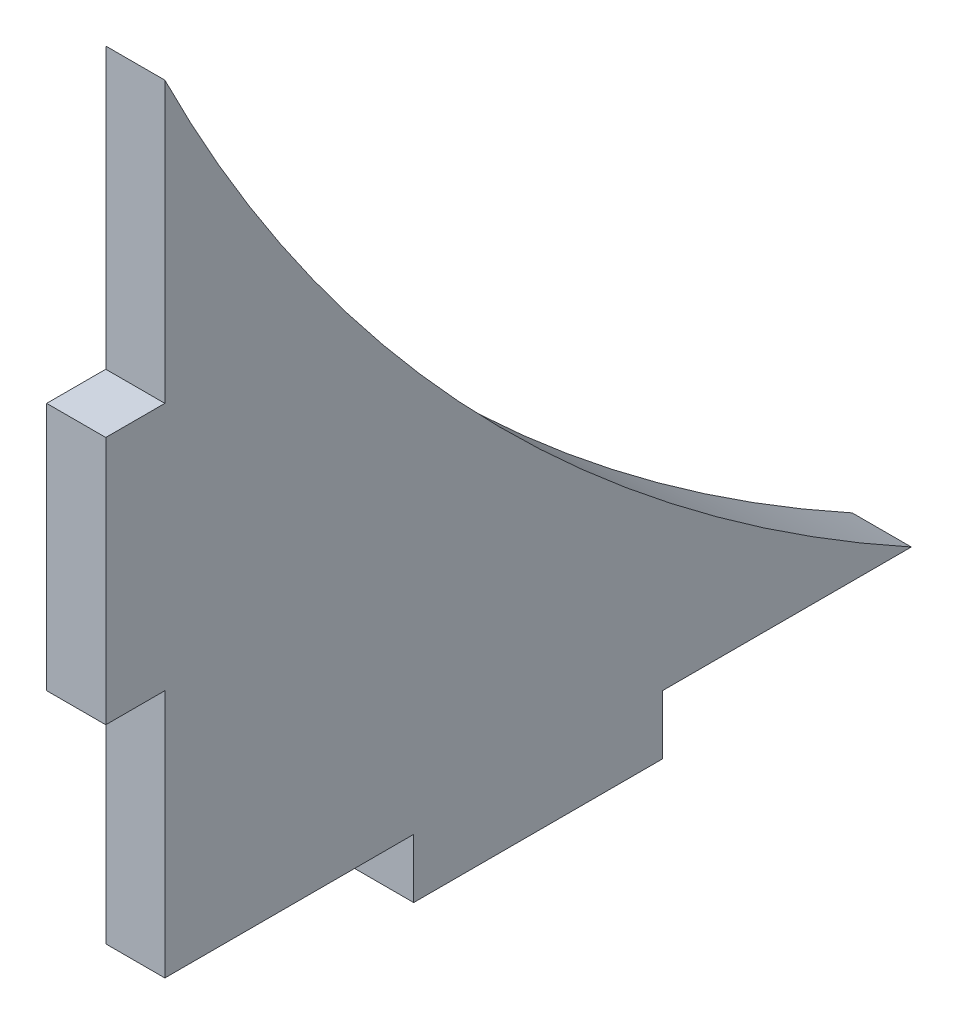
SolidWorks part; units mm, degrees
ref_plane "Front Plane" through (0, 0, 0) normal (0, 0, 1) x (1, 0, 0)
ref_plane "Top Plane" through (0, 0, 0) normal (0, 1, 0) x (1, 0, 0)
ref_plane "Right Plane" through (0, 0, 0) normal (1, 0, 0) x (0, 0, -1)
sketch "Sketch1" plane through (0, 0, 0) normal (1, 0, 0) x (0, 0, -1)
  line L0 (-143.7729, 109.4322) -> (-143.7729, -140.5678)
  line L1 (-143.7729, -140.5678) -> (96.2271, -140.5678)
  arc A0 (-143.7729, 109.4322) -> (96.2271, -140.5678) centre (373.8498, 366.15) ccw
  dimension "D1" = 250
  dimension "D2" = 240
extrude "Boss-Extrude1" add sketch "Sketch1" along normal blind 19
sketch "Sketch2" plane through (0, -140.5678, 0) normal (0, -1, 0) x (1, 0, 0)
  line L0 (0, 143.7729) -> (0, -96.2271) construction
  line L1 (0, 63.7729) -> (19, 63.7729)
  line L2 (0, 63.7729) -> (0, -16.2271)
  line L3 (0, -16.2271) -> (19, -16.2271)
  line L4 (19, 63.7729) -> (19, -16.2271)
  line L5 (19, 143.7729) -> (19, -96.2271) construction
  line L7 (19, 143.7729) -> (0, 143.7729) construction
  dimension "D2" = 80
extrude "Boss-Extrude2" add sketch "Sketch2" along normal blind 19
sketch "Sketch3" plane through (0, 0, 143.7729) normal (0, 0, 1) x (1, 0, 0)
  line L0 (0, 109.4322) -> (0, -140.5678) construction
  line L1 (0, 19.4322) -> (19, 19.4322)
  line L2 (0, 19.4322) -> (0, -60.5678)
  line L3 (0, -60.5678) -> (19, -60.5678)
  line L4 (19, 19.4322) -> (19, -60.5678)
  line L5 (19, 109.4322) -> (19, -140.5678) construction
  line L6 (19, -140.5678) -> (0, -140.5678) construction
  dimension "D1" = 80
extrude "Boss-Extrude3" add sketch "Sketch3" along normal blind 19
